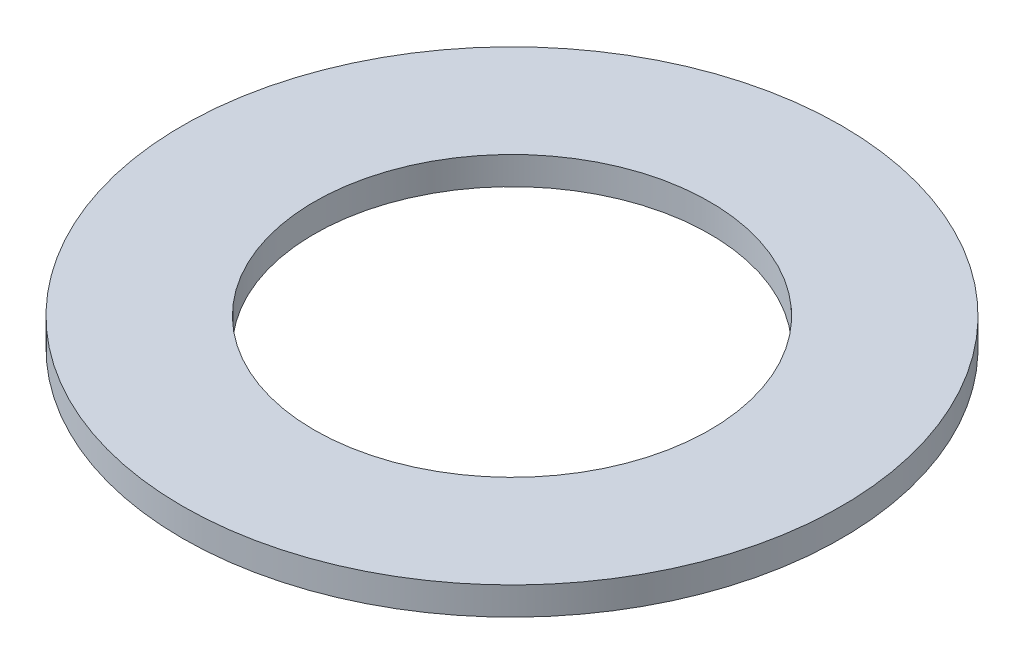
SolidWorks part; units mm, degrees
ref_plane "Front Plane" through (0, 0, 0) normal (0, 0, 1) x (1, 0, 0)
ref_plane "Top Plane" through (0, 0, 0) normal (0, 1, 0) x (1, 0, 0)
ref_plane "Right Plane" through (0, 0, 0) normal (1, 0, 0) x (0, 0, -1)
sketch "Sketch1" plane through (0, 0, 0) normal (0, 1, 0) x (1, 0, 0)
  circle A0 centre (0, 0) radius 75
  dimension "D1" = 150
extrude "Boss-Extrude1" add sketch "Sketch1" along normal blind 6.35
sketch "Sketch2" plane through (0, 6.35, 0) normal (0, 1, 0) x (1, 0, 0)
  circle A0 centre (0, 0) radius 45
  dimension "D1" = 90
extrude "Cut-Extrude1" cut sketch "Sketch2" against normal through all contours A0
